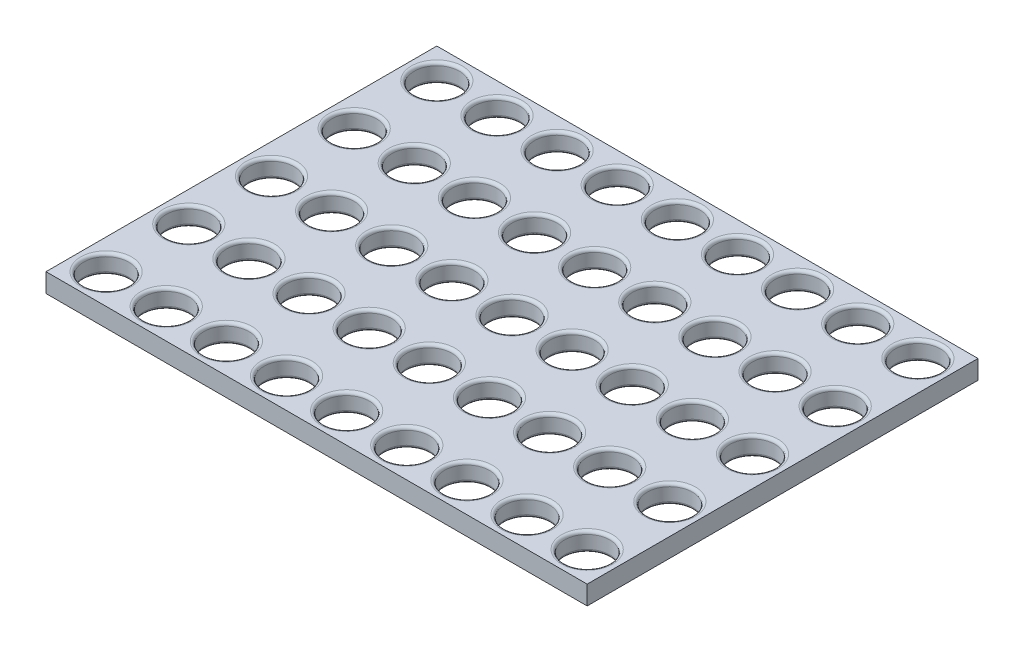
SolidWorks part; units mm, degrees
ref_plane "Front Plane" through (0, 0, 0) normal (0, 0, 1) x (1, 0, 0)
ref_plane "Top Plane" through (0, 0, 0) normal (0, 1, 0) x (1, 0, 0)
ref_plane "Right Plane" through (0, 0, 0) normal (1, 0, 0) x (0, 0, -1)
sketch "Sketch1" plane through (0, 0, 0) normal (0, 1, 0) x (1, 0, 0)
  line L1 (-18.3995, 12.9633) -> (27.3205, 12.9633)
  line L2 (-18.3995, 12.9633) -> (-18.3995, -20.0567)
  line L3 (-18.3995, -20.0567) -> (27.3205, -20.0567)
  line L4 (27.3205, 12.9633) -> (27.3205, -20.0567)
  dimension "D1" = 45.72
  dimension "D2" = 33.02
extrude "Boss-Extrude1" add sketch "Sketch1" along normal blind 1.6
sketch "Sketch2" plane through (0, 1.6, 0) normal (0, 1, 0) x (1, 0, 0)
  line L0 (-18.3995, 12.9633) -> (-18.3995, -20.0567) construction
  line L1 (27.3205, 12.9633) -> (-18.3995, 12.9633) construction
  circle A0 centre (-15.8595, 10.4233) radius 1.905
  circle A1 centre (-10.7795, 10.4233) radius 1.905
  circle A2 centre (-5.6995, 10.4233) radius 1.905
  circle A3 centre (-0.6195, 10.4233) radius 1.905
  circle A4 centre (4.4605, 10.4233) radius 1.905
  circle A5 centre (9.5405, 10.4233) radius 1.905
  circle A6 centre (14.6205, 10.4233) radius 1.905
  circle A7 centre (19.7005, 10.4233) radius 1.905
  circle A8 centre (24.7805, 10.4233) radius 1.905
  circle A9 centre (-10.7795, 3.4383) radius 1.905
  circle A10 centre (-5.6995, 3.4383) radius 1.905
  circle A11 centre (-0.6195, 3.4383) radius 1.905
  circle A12 centre (4.4605, 3.4383) radius 1.905
  circle A13 centre (9.5405, 3.4383) radius 1.905
  circle A14 centre (14.6205, 3.4383) radius 1.905
  circle A15 centre (19.7005, 3.4383) radius 1.905
  circle A16 centre (24.7805, 3.4383) radius 1.905
  circle A17 centre (-10.7795, -3.5467) radius 1.905
  circle A18 centre (-5.6995, -3.5467) radius 1.905
  circle A19 centre (-0.6195, -3.5467) radius 1.905
  circle A20 centre (4.4605, -3.5467) radius 1.905
  circle A21 centre (9.5405, -3.5467) radius 1.905
  circle A22 centre (14.6205, -3.5467) radius 1.905
  circle A23 centre (19.7005, -3.5467) radius 1.905
  circle A24 centre (24.7805, -3.5467) radius 1.905
  circle A25 centre (-10.7795, -10.5317) radius 1.905
  circle A26 centre (-5.6995, -10.5317) radius 1.905
  circle A27 centre (-0.6195, -10.5317) radius 1.905
  circle A28 centre (4.4605, -10.5317) radius 1.905
  circle A29 centre (9.5405, -10.5317) radius 1.905
  circle A30 centre (14.6205, -10.5317) radius 1.905
  circle A31 centre (19.7005, -10.5317) radius 1.905
  circle A32 centre (24.7805, -10.5317) radius 1.905
  circle A33 centre (-10.7795, -17.5167) radius 1.905
  circle A34 centre (-5.6995, -17.5167) radius 1.905
  circle A35 centre (-0.6195, -17.5167) radius 1.905
  circle A36 centre (4.4605, -17.5167) radius 1.905
  circle A37 centre (9.5405, -17.5167) radius 1.905
  circle A38 centre (14.6205, -17.5167) radius 1.905
  circle A39 centre (19.7005, -17.5167) radius 1.905
  circle A40 centre (24.7805, -17.5167) radius 1.905
  circle A41 centre (-15.8595, 3.4383) radius 1.905
  circle A42 centre (-15.8595, -3.5467) radius 1.905
  circle A43 centre (-15.8595, -10.5317) radius 1.905
  circle A44 centre (-15.8595, -17.5167) radius 1.905
  dimension "D1" = 3.81
  dimension "D2" = 2.54
  dimension "D3" = 2.54
  dimension "D4" = 9
  dimension "D5" = 5
extrude "Cut-Extrude2" cut sketch "Sketch2" against normal blind 1.6
fillet "Fillet3" radius 0.254 90 edges at (-15.8595, 0, -8.5183) (-15.8595, 0, 19.4217) (-15.8595, 0, 12.4367) (-15.8595, 0, 5.4517) (24.7805, 0, 19.4217) (19.7005, 0, 19.4217) (14.6205, 0, 19.4217) (9.5405, 0, 19.4217) (4.4605, 0, 19.4217) (-0.6195, 0, 19.4217) (-5.6995, 0, 19.4217) (-10.7795, 0, 19.4217) (24.7805, 0, 12.4367) (19.7005, 0, 12.4367) (14.6205, 0, 12.4367) (9.5405, 0, 12.4367) (4.4605, 0, 12.4367) (-0.6195, 0, 12.4367) (-5.6995, 0, 12.4367) (-10.7795, 0, 12.4367) (24.7805, 0, 5.4517) (19.7005, 0, 5.4517) (14.6205, 0, 5.4517) (9.5405, 0, 5.4517) (4.4605, 0, 5.4517) (-0.6195, 0, 5.4517) (-5.6995, 0, 5.4517) (-10.7795, 0, 5.4517) (24.7805, 0, -1.5333) (19.7005, 0, -1.5333) (14.6205, 0, -1.5333) (9.5405, 0, -1.5333) (4.4605, 0, -1.5333) (-0.6195, 0, -1.5333) (-5.6995, 0, -1.5333) (24.7805, 0, -8.5183) (19.7005, 0, -8.5183) (14.6205, 0, -8.5183) (9.5405, 0, -8.5183) (4.4605, 0, -8.5183) (-0.6195, 0, -8.5183) (-5.6995, 0, -8.5183) (-10.7795, 0, -8.5183) (-10.7795, 0, -1.5333) (-15.8595, 0, -1.5333) (24.7805, 1.6, 19.4217) (19.7005, 1.6, 19.4217) (14.6205, 1.6, 19.4217) (9.5405, 1.6, 19.4217) (4.4605, 1.6, 19.4217) (-0.6195, 1.6, 19.4217) (24.7805, 1.6, 12.4367) (19.7005, 1.6, 12.4367) (14.6205, 1.6, 12.4367) (9.5405, 1.6, 12.4367) (24.7805, 1.6, 5.4517) (19.7005, 1.6, 5.4517) (14.6205, 1.6, 5.4517) (9.5405, 1.6, 5.4517) (24.7805, 1.6, -1.5333) (19.7005, 1.6, -1.5333) (14.6205, 1.6, -1.5333) (9.5405, 1.6, -1.5333) (-0.6195, 1.6, -1.5333) (4.4605, 1.6, -1.5333) (-0.6195, 1.6, 5.4517) (4.4605, 1.6, 5.4517) (4.4605, 1.6, 12.4367) (-0.6195, 1.6, 12.4367) (-5.6995, 1.6, 19.4217) (-5.6995, 1.6, -1.5333) (-5.6995, 1.6, 5.4517) (-5.6995, 1.6, 12.4367) (-10.7795, 1.6, 19.4217) (-10.7795, 1.6, 12.4367) (-10.7795, 1.6, 5.4517) (-10.7795, 1.6, -1.5333) (-15.8595, 1.6, 19.4217) (-15.8595, 1.6, 12.4367) (-15.8595, 1.6, 5.4517) (-15.8595, 1.6, -1.5333) (24.7805, 1.6, -8.5183) (19.7005, 1.6, -8.5183) (14.6205, 1.6, -8.5183) (9.5405, 1.6, -8.5183) (4.4605, 1.6, -8.5183) (-0.6195, 1.6, -8.5183) (-5.6995, 1.6, -8.5183) (-10.7795, 1.6, -8.5183) (-15.8595, 1.6, -8.5183)
